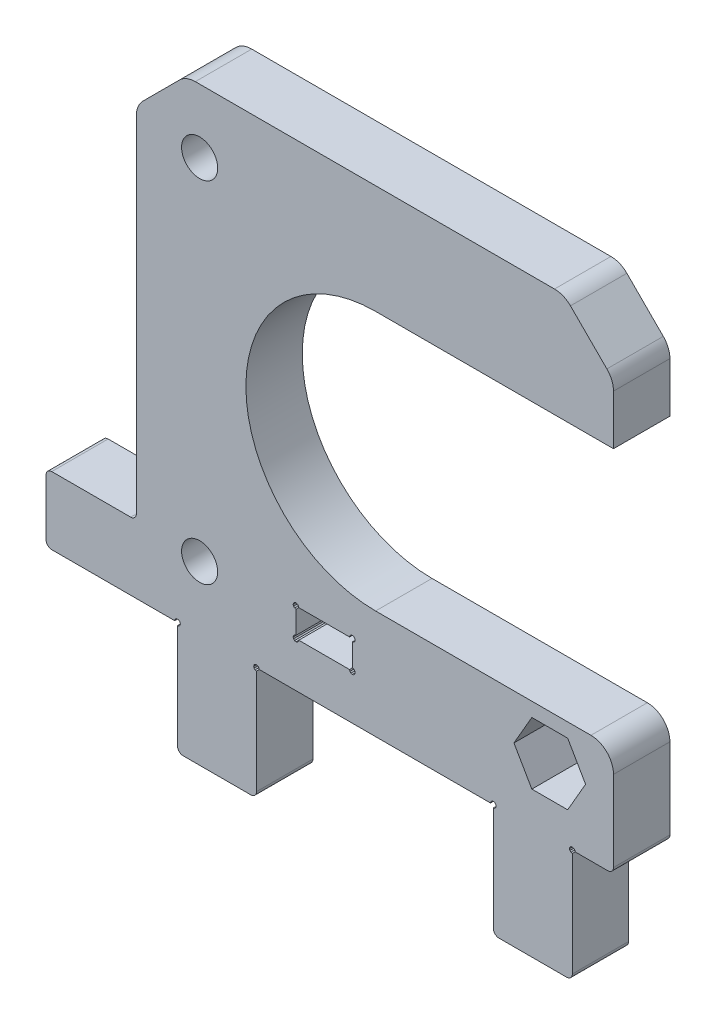
SolidWorks part; units mm, degrees
ref_plane "Plan de face" through (0, 0, 0) normal (0, 0, 1) x (1, 0, 0)
ref_plane "Plan de dessus" through (0, 0, 0) normal (0, 1, 0) x (1, 0, 0)
ref_plane "Plan de droite" through (0, 0, 0) normal (1, 0, 0) x (0, 0, -1)
ref_plane "Plan1" through (0, 0, 0) normal (0, 0, -1) x (-1, 0, 0)
sketch "Esquisse1" plane through (0, 0, 0) normal (0, 0, -1) x (-1, 0, 0)
  line L1 (-13.2284, 52.3) -> (-45.0715, 52.3)
  line L4 (-46.4857, 51.7142) -> (-49.7142, 48.4858)
  line L7 (-50.3, 47.0716) -> (-50.3, 42.65)
  line L8 (-50.3, 42.65) -> (-29.21, 42.65)
  line L23 (-29.21, 19.65) -> (-48.3, 19.65)
  line L27 (-50.3, 17.65) -> (-50.3, 10.5)
  line L31 (-49.8, 10) -> (-46.9, 10)
  line L32 (-46.9, 10) -> (-46.8665, 10.125)
  line L33 (-46.8665, 10.125) -> (-46.775, 10.2165)
  line L34 (-46.775, 10.2165) -> (-46.65, 10.25)
  line L35 (-46.65, 10.25) -> (-46.525, 10.2165)
  line L36 (-46.525, 10.2165) -> (-46.4334, 10.125)
  line L37 (-46.4334, 10.125) -> (-46.4, 10)
  line L38 (-46.4, 10) -> (-46.4334, 9.875)
  line L39 (-46.4334, 9.875) -> (-46.525, 9.7835)
  line L40 (-46.525, 9.7835) -> (-46.65, 9.75)
  line L41 (-46.65, 9.75) -> (-46.65, 0.5)
  line L45 (-46.15, 0) -> (-40.15, 0)
  line L49 (-39.65, 0.5) -> (-39.65, 9.75)
  line L50 (-39.65, 9.75) -> (-39.775, 9.7835)
  line L51 (-39.775, 9.7835) -> (-39.8665, 9.875)
  line L52 (-39.8665, 9.875) -> (-39.9, 10)
  line L53 (-39.9, 10) -> (-39.8665, 10.125)
  line L54 (-39.8665, 10.125) -> (-39.775, 10.2165)
  line L55 (-39.775, 10.2165) -> (-39.65, 10.25)
  line L56 (-39.65, 10.25) -> (-39.525, 10.2165)
  line L57 (-39.525, 10.2165) -> (-39.4334, 10.125)
  line L58 (-39.4334, 10.125) -> (-39.4, 10)
  line L59 (-39.4, 10) -> (-18.9, 10)
  line L60 (-18.9, 10) -> (-18.8665, 10.125)
  line L61 (-18.8665, 10.125) -> (-18.775, 10.2165)
  line L62 (-18.775, 10.2165) -> (-18.65, 10.25)
  line L63 (-18.65, 10.25) -> (-18.525, 10.2165)
  line L64 (-18.525, 10.2165) -> (-18.4334, 10.125)
  line L65 (-18.4334, 10.125) -> (-18.4, 10)
  line L66 (-18.4, 10) -> (-18.4334, 9.875)
  line L67 (-18.4334, 9.875) -> (-18.525, 9.7835)
  line L68 (-18.525, 9.7835) -> (-18.65, 9.75)
  line L69 (-18.65, 9.75) -> (-18.65, 0.5)
  line L73 (-18.15, 0) -> (-12.1499, 0)
  line L77 (-11.6499, 0.5) -> (-11.6499, 9.75)
  line L78 (-11.6499, 9.75) -> (-11.7749, 9.7835)
  line L79 (-11.7749, 9.7835) -> (-11.8665, 9.875)
  line L80 (-11.8665, 9.875) -> (-11.8999, 10)
  line L81 (-11.8999, 10) -> (-11.8665, 10.125)
  line L82 (-11.8665, 10.125) -> (-11.7749, 10.2165)
  line L83 (-11.7749, 10.2165) -> (-11.6499, 10.25)
  line L84 (-11.6499, 10.25) -> (-11.5249, 10.2165)
  line L85 (-11.5249, 10.2165) -> (-11.4334, 10.125)
  line L86 (-11.4334, 10.125) -> (-11.3999, 10)
  line L87 (-11.3999, 10) -> (-0.4999, 10)
  line L91 (0.0001, 10.5) -> (0.0001, 15.5)
  line L95 (-0.4999, 16) -> (-7.4999, 16)
  line L99 (-7.9999, 16.5) -> (-7.9999, 47.0716)
  line L102 (-8.5857, 48.4858) -> (-11.8142, 51.7142)
  line L116 (-22.025, 14.2165) -> (-21.9335, 14.125)
  line L117 (-21.9335, 14.125) -> (-21.9, 14)
  line L118 (-21.9, 14) -> (-21.9335, 13.875)
  line L119 (-21.9335, 13.875) -> (-22.025, 13.7835)
  line L120 (-22.025, 13.7835) -> (-22.15, 13.75)
  line L121 (-22.15, 13.75) -> (-22.275, 13.7835)
  line L122 (-22.275, 13.7835) -> (-22.3665, 13.875)
  line L123 (-22.3665, 13.875) -> (-22.4, 14)
  line L124 (-22.4, 14) -> (-26.9, 14)
  line L125 (-26.9, 14) -> (-26.9335, 13.875)
  line L126 (-26.9335, 13.875) -> (-27.025, 13.7835)
  line L127 (-27.025, 13.7835) -> (-27.15, 13.75)
  line L128 (-27.15, 13.75) -> (-27.275, 13.7835)
  line L129 (-27.275, 13.7835) -> (-27.3665, 13.875)
  line L130 (-27.3665, 13.875) -> (-27.4, 14)
  line L131 (-27.4, 14) -> (-27.3665, 14.125)
  line L132 (-27.3665, 14.125) -> (-27.275, 14.2165)
  line L133 (-27.275, 14.2165) -> (-27.15, 14.25)
  line L134 (-27.15, 14.25) -> (-27.15, 16.25)
  line L135 (-27.15, 16.25) -> (-27.275, 16.2835)
  line L136 (-27.275, 16.2835) -> (-27.3665, 16.375)
  line L137 (-27.3665, 16.375) -> (-27.4, 16.5)
  line L138 (-27.4, 16.5) -> (-27.3665, 16.625)
  line L139 (-27.3665, 16.625) -> (-27.275, 16.7165)
  line L140 (-27.275, 16.7165) -> (-27.15, 16.75)
  line L141 (-27.15, 16.75) -> (-27.025, 16.7165)
  line L142 (-27.025, 16.7165) -> (-26.9335, 16.625)
  line L143 (-26.9335, 16.625) -> (-26.9, 16.5)
  line L144 (-26.9, 16.5) -> (-22.4, 16.5)
  line L145 (-22.4, 16.5) -> (-22.3665, 16.625)
  line L146 (-22.3665, 16.625) -> (-22.275, 16.7165)
  line L147 (-22.275, 16.7165) -> (-22.15, 16.75)
  line L148 (-22.15, 16.75) -> (-22.025, 16.7165)
  line L149 (-22.025, 16.7165) -> (-21.9335, 16.625)
  line L150 (-21.9335, 16.625) -> (-21.9, 16.5)
  line L151 (-21.9, 16.5) -> (-21.9335, 16.375)
  line L152 (-21.9335, 16.375) -> (-22.025, 16.2835)
  line L153 (-22.025, 16.2835) -> (-22.15, 16.25)
  line L154 (-22.15, 16.25) -> (-22.15, 14.25)
  line L155 (-22.15, 14.25) -> (-22.025, 14.2165)
  line L168 (-43.0623, 18.4) -> (-41.4746, 15.65)
  line L169 (-41.4746, 15.65) -> (-43.0623, 12.9)
  line L170 (-43.0623, 12.9) -> (-46.2377, 12.9)
  line L171 (-46.2377, 12.9) -> (-47.8254, 15.65)
  line L172 (-47.8254, 15.65) -> (-46.2377, 18.4)
  line L173 (-46.2377, 18.4) -> (-43.0623, 18.4)
  arc A0 (-29.21, 19.65) -> (-29.21, 42.65) centre (-29.21, 31.15) ccw
  circle A1 centre (-13.61, 46.65) radius 1.6
  circle A2 centre (-13.61, 15.65) radius 1.6
  arc A3 (0.0001, 15.5) -> (-0.4999, 16) centre (-0.4999, 15.5) ccw
  arc A4 (-7.4999, 16) -> (-7.9999, 16.5) centre (-7.4999, 16.5) cw
  arc A5 (0.0001, 10.5) -> (-0.4999, 10) centre (-0.4999, 10.5) cw
  arc A6 (-11.6499, 0.5) -> (-12.1499, 0) centre (-12.1499, 0.5) cw
  arc A7 (-18.15, 0) -> (-18.65, 0.5) centre (-18.15, 0.5) cw
  arc A8 (-39.65, 0.5) -> (-40.15, 0) centre (-40.15, 0.5) cw
  arc A9 (-46.15, 0) -> (-46.65, 0.5) centre (-46.15, 0.5) cw
  arc A10 (-49.8, 10) -> (-50.3, 10.5) centre (-49.8, 10.5) cw
  arc A11 (-50.3, 17.65) -> (-48.3, 19.65) centre (-48.3, 17.65) cw
  arc A12 (-45.0715, 52.3) -> (-46.4857, 51.7142) centre (-45.0715, 50.3) ccw
  arc A13 (-49.7142, 48.4858) -> (-50.3, 47.0716) centre (-48.2999, 47.0716) ccw
  arc A14 (-7.9999, 47.0716) -> (-8.5857, 48.4858) centre (-10, 47.0716) ccw
  arc A15 (-11.8142, 51.7142) -> (-13.2284, 52.3) centre (-13.2284, 50.3) ccw
  dimension "D1" = 23
  dimension "D2" = 3.2
  dimension "D3" = 3.2
  dimension "D5" = 15.5
  dimension "D6" = 15.6
  dimension "D7" = 15.6
  dimension "D4" = 31
  dimension "D8" = 31.15
  dimension "D9" = 29.21
extrude "Boss.-Extru.1" add sketch "Esquisse1" against normal blind 5
